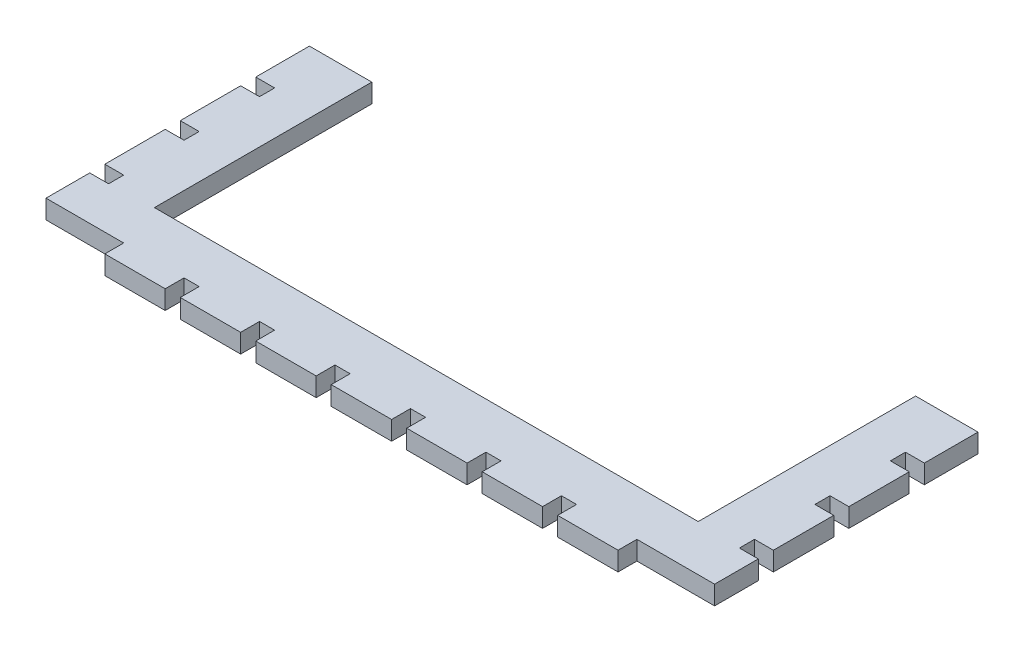
SolidWorks part; units mm, degrees
ref_plane "Front Plane" through (0, 0, 0) normal (0, 0, 1) x (1, 0, 0)
ref_plane "Top Plane" through (0, 0, 0) normal (0, 1, 0) x (1, 0, 0)
ref_plane "Right Plane" through (0, 0, 0) normal (1, 0, 0) x (0, 0, -1)
sketch "Sketch1" plane through (0, 0, 0) normal (0, 1, 0) x (1, 0, 0)
  line L48 (32.1429, 0) -> (32.1429, 6.35)
  line L49 (0, 0) -> (32.1429, 0)
  line L50 (0, 0) -> (0, 6.35)
  line L51 (0, 6.35) -> (32.1429, 6.35)
  line L52 (32.1429, 0) -> (32.1429, 6.35)
  line L53 (0, 0) -> (6.35, 0)
  line L54 (0, 0) -> (0, 32.1429)
  line L55 (0, 32.1429) -> (6.35, 32.1429)
  line L56 (6.35, 0) -> (6.35, 32.1429)
  line L57 (32.1429, 0) -> (64.2857, 0)
  line L58 (64.2857, 0) -> (64.2857, 6.35)
  line L59 (32.1429, 6.35) -> (64.2857, 6.35)
  line L60 (64.2857, 0) -> (64.2857, 6.35)
  line L61 (64.2857, 0) -> (96.4286, 0)
  line L62 (96.4286, 0) -> (96.4286, 6.35)
  line L63 (64.2857, 6.35) -> (96.4286, 6.35)
  line L64 (96.4286, 0) -> (96.4286, 6.35)
  line L65 (96.4286, 0) -> (128.5714, 0)
  line L66 (128.5714, 0) -> (128.5714, 6.35)
  line L67 (96.4286, 6.35) -> (128.5714, 6.35)
  line L72 (128.5714, 0) -> (128.5714, 6.35)
  line L73 (128.5714, 0) -> (160.7143, 0)
  line L74 (160.7143, 0) -> (160.7143, 6.35)
  line L75 (128.5714, 6.35) -> (160.7143, 6.35)
  line L76 (160.7143, 0) -> (160.7143, 6.35)
  line L77 (160.7143, 0) -> (192.8571, 0)
  line L78 (192.8571, 0) -> (192.8571, 6.35)
  line L79 (160.7143, 6.35) -> (192.8571, 6.35)
  line L80 (192.8571, 0) -> (192.8571, 6.35)
  line L81 (192.8571, 0) -> (225, 0)
  line L82 (225, 0) -> (225, 6.35)
  line L83 (192.8571, 6.35) -> (225, 6.35)
  line L84 (0, 32.1429) -> (0, 64.2857)
  line L85 (0, 32.1429) -> (6.35, 32.1429)
  line L86 (6.35, 32.1429) -> (6.35, 64.2857)
  line L87 (0, 64.2857) -> (6.35, 64.2857)
  line L88 (0, 64.2857) -> (0, 96.4286)
  line L89 (0, 64.2857) -> (6.35, 64.2857)
  line L90 (6.35, 64.2857) -> (6.35, 96.4286)
  line L91 (0, 96.4286) -> (6.35, 96.4286)
  line L98 (0, 96.4286) -> (0, 128.5714)
  line L99 (0, 96.4286) -> (6.35, 96.4286)
  line L100 (6.35, 96.4286) -> (6.35, 128.5714)
  line L101 (0, 128.5714) -> (6.35, 128.5714)
  line L102 (0, 128.5714) -> (0, 160.7143)
  line L103 (0, 128.5714) -> (6.35, 128.5714)
  line L104 (6.35, 128.5714) -> (6.35, 160.7143)
  line L105 (0, 160.7143) -> (6.35, 160.7143)
  line L106 (0, 160.7143) -> (0, 192.8571)
  line L107 (0, 160.7143) -> (6.35, 160.7143)
  line L108 (6.35, 160.7143) -> (6.35, 192.8571)
  line L109 (0, 192.8571) -> (6.35, 192.8571)
  line L110 (0, 192.8571) -> (0, 225)
  line L111 (0, 192.8571) -> (6.35, 192.8571)
  line L112 (6.35, 192.8571) -> (6.35, 225)
  line L113 (0, 225) -> (6.35, 225)
  line L114 (112.5, 0) -> (112.5, 671.069) construction
  line L115 (-187.856, 112.5) -> (254.8092, 112.5) construction
  line L116 (225, 32.1429) -> (218.65, 32.1429)
  line L117 (218.65, 0) -> (218.65, 32.1429)
  line L118 (225, 0) -> (218.65, 0)
  line L119 (225, 0) -> (225, 32.1429)
  line L120 (225, 192.8571) -> (218.65, 192.8571)
  line L121 (218.65, 192.8571) -> (218.65, 225)
  line L122 (225, 225) -> (218.65, 225)
  line L123 (225, 192.8571) -> (225, 225)
  line L124 (225, 160.7143) -> (218.65, 160.7143)
  line L125 (218.65, 160.7143) -> (218.65, 192.8571)
  line L126 (225, 192.8571) -> (218.65, 192.8571)
  line L127 (225, 160.7143) -> (225, 192.8571)
  line L128 (225, 32.1429) -> (218.65, 32.1429)
  line L129 (218.65, 32.1429) -> (218.65, 64.2857)
  line L130 (225, 64.2857) -> (218.65, 64.2857)
  line L131 (225, 32.1429) -> (225, 64.2857)
  line L132 (225, 128.5714) -> (218.65, 128.5714)
  line L133 (218.65, 128.5714) -> (218.65, 160.7143)
  line L134 (225, 160.7143) -> (218.65, 160.7143)
  line L135 (225, 128.5714) -> (225, 160.7143)
  line L136 (225, 96.4286) -> (218.65, 96.4286)
  line L137 (218.65, 96.4286) -> (218.65, 128.5714)
  line L138 (225, 128.5714) -> (218.65, 128.5714)
  line L139 (225, 96.4286) -> (225, 128.5714)
  line L140 (225, 64.2857) -> (218.65, 64.2857)
  line L141 (218.65, 64.2857) -> (218.65, 96.4286)
  line L142 (225, 96.4286) -> (218.65, 96.4286)
  line L143 (225, 64.2857) -> (225, 96.4286)
  line L144 (192.8571, 225) -> (225, 225)
  line L145 (225, 225) -> (225, 218.65)
  line L146 (192.8571, 218.65) -> (225, 218.65)
  line L147 (192.8571, 225) -> (192.8571, 218.65)
  line L148 (160.7143, 225) -> (192.8571, 225)
  line L149 (192.8571, 225) -> (192.8571, 218.65)
  line L150 (160.7143, 218.65) -> (192.8571, 218.65)
  line L151 (160.7143, 225) -> (160.7143, 218.65)
  line L152 (128.5714, 225) -> (160.7143, 225)
  line L153 (160.7143, 225) -> (160.7143, 218.65)
  line L154 (128.5714, 218.65) -> (160.7143, 218.65)
  line L155 (128.5714, 225) -> (128.5714, 218.65)
  line L156 (96.4286, 225) -> (128.5714, 225)
  line L157 (128.5714, 225) -> (128.5714, 218.65)
  line L158 (96.4286, 218.65) -> (128.5714, 218.65)
  line L159 (96.4286, 225) -> (96.4286, 218.65)
  line L160 (64.2857, 225) -> (96.4286, 225)
  line L161 (96.4286, 225) -> (96.4286, 218.65)
  line L162 (64.2857, 218.65) -> (96.4286, 218.65)
  line L163 (64.2857, 225) -> (64.2857, 218.65)
  line L164 (32.1429, 225) -> (64.2857, 225)
  line L165 (64.2857, 225) -> (64.2857, 218.65)
  line L166 (32.1429, 218.65) -> (64.2857, 218.65)
  line L167 (32.1429, 225) -> (32.1429, 218.65)
  line L168 (0, 218.65) -> (32.1429, 218.65)
  line L169 (32.1429, 225) -> (32.1429, 218.65)
  line L170 (0, 225) -> (32.1429, 225)
  line L171 (0, 225) -> (0, 218.65)
  point P56 (112.5, 6.35)
  point P58 (6.35, 112.5)
  dimension "D3" = 112.5
  dimension "D4" = 112.5
  dimension "D5" = 6.35
  dimension "D2" = 7
  dimension "D1" = 7
extrude "Boss-Extrude1" add sketch "Sketch1" along normal blind 6.35 contours L168 L112 L108 L104 L100 L90 L86 L56 L51 L59 L63 L67 L75 L79 L83 L117 L129 L141 L137 L133 L125 L121 L146 L150 L154 L158 L162 L166 | L164 L167 L166 L163 | L156 L159 L158 L155 | L148 L151 L150 L147 | L79 L74 L77 L78 | L67 L62 L65 L66 | L59 L48 L57 L58
sketch "Sketch2" plane through (0, 6.35, 0) normal (0, 1, 0) x (1, 0, 0)
  line L0 (218.65, 112.5) -> (6.35, 112.5) construction
  line L1 (218.65, 6.35) -> (218.65, 218.65) construction
  line L2 (6.35, 6.35) -> (6.35, 218.65) construction
  line L3 (160.7143, 225) -> (192.8571, 225) construction
  line L4 (6.35, 112.5) -> (218.65, 112.5)
  line L5 (6.35, 112.5) -> (6.35, 225)
  line L6 (6.35, 225) -> (218.65, 225)
  line L7 (218.65, 112.5) -> (218.65, 225)
extrude "Cut-Extrude1" cut sketch "Sketch2" against normal through all
sketch "Sketch3" plane through (0, 6.35, 0) normal (0, 1, 0) x (1, 0, 0)
  line L1 (6.35, 112.5) -> (218.65, 112.5)
  line L2 (6.35, 112.5) -> (6.35, 95)
  line L3 (6.35, 95) -> (218.65, 95)
  line L4 (218.65, 112.5) -> (218.65, 95)
  line L5 (218.65, 6.35) -> (218.65, 112.5) construction
  line L6 (192.8571, 6.35) -> (218.65, 6.35) construction
  point P5 (218.65, 77.2727)
  point P7 (0, 0)
  dimension "D1" = 88.65
extrude "Cut-Extrude2" cut sketch "Sketch3" against normal up to surface (6.35 mm away) up to face at (112.5, 0, -17.2375)
sketch "Sketch4" plane through (0, 6.35, 0) normal (0, 1, 0) x (1, 0, 0)
  line L0 (6.35, 6.35) -> (6.35, 95) construction
  line L1 (6.35, 26.14) -> (0, 26.14)
  line L2 (6.35, 26.14) -> (6.35, 46.46)
  line L3 (6.35, 46.46) -> (0, 46.46)
  line L4 (0, 26.14) -> (0, 46.46)
  line L5 (6.35, 95) -> (0, 95)
  line L6 (6.35, 51.54) -> (0, 51.54)
  line L7 (6.35, 51.54) -> (6.35, 71.86)
  line L8 (6.35, 71.86) -> (0, 71.86)
  line L9 (0, 51.54) -> (0, 71.86)
  line L10 (6.35, 76.94) -> (0, 76.94)
  line L11 (6.35, 76.94) -> (6.35, 97.26)
  line L12 (6.35, 97.26) -> (0, 97.26)
  line L13 (0, 76.94) -> (0, 97.26)
  line L14 (6.35, 6.35) -> (0, 6.35)
  line L15 (6.35, 6.35) -> (6.35, 21.06)
  line L16 (6.35, 21.06) -> (0, 21.06)
  line L17 (0, 6.35) -> (0, 21.06)
  line L18 (112.5, 0) -> (112.5, 95) construction
  line L19 (96.4286, 0) -> (128.5714, 0) construction
  line L20 (6.35, 95) -> (218.65, 95) construction
  line L21 (225, 6.35) -> (225, 21.06)
  line L22 (218.65, 21.06) -> (225, 21.06)
  line L23 (218.65, 6.35) -> (218.65, 21.06)
  line L24 (218.65, 6.35) -> (225, 6.35)
  line L25 (225, 76.94) -> (225, 97.26)
  line L26 (218.65, 97.26) -> (225, 97.26)
  line L27 (218.65, 76.94) -> (218.65, 97.26)
  line L28 (218.65, 76.94) -> (225, 76.94)
  line L29 (225, 51.54) -> (225, 71.86)
  line L30 (218.65, 71.86) -> (225, 71.86)
  line L31 (218.65, 51.54) -> (218.65, 71.86)
  line L32 (218.65, 51.54) -> (225, 51.54)
  line L33 (218.65, 95) -> (225, 95)
  line L34 (225, 26.14) -> (225, 46.46)
  line L35 (218.65, 46.46) -> (225, 46.46)
  line L36 (218.65, 26.14) -> (218.65, 46.46)
  line L37 (218.65, 26.14) -> (225, 26.14)
  line L38 (225, 95) -> (218.65, 95)
  line L40 (225, 95) -> (218.65, 95)
  line L41 (225, 95) -> (225, 76.94)
  line L42 (225, 76.94) -> (218.65, 76.94)
  line L43 (218.65, 95) -> (218.65, 76.94)
  line M18 (6.35, 95) -> (6.35, 6.35)
  dimension "D1" = 20.32
  dimension "D2" = 5.08
  dimension "D3" = 5.08
  dimension "D4" = 5.08
  dimension "D5" = 14.71
  dimension "D6" = 6.35
extrude "Boss-Extrude2" add sketch "Sketch4" against normal up to surface (6.35 mm away) contours L13 L10 L5 M18 | L9 L6 L8 M18 | L4 L1 L3 M18 | L17 L14 L16 M18 | L41 L40 L43 L42 | L29 L30 L31 L32 | L34 L35 L36 L37 | L21 L22 L23 L24 up to face at (112.5, 0, -15.05)
sketch "Sketch5" plane through (0, 0, 0) normal (0, -1, 0) x (1, 0, 0)
  line L0 (225, -95) -> (0, -95) construction
  line L1 (204, -95) -> (21, -95)
  line L2 (204, -95) -> (204, -21.844)
  line L3 (204, -21.844) -> (21, -21.844)
  line L4 (21, -95) -> (21, -21.844)
  line L5 (112.5, 0) -> (112.5, -133.1244) construction
  line L7 (96.4286, 0) -> (128.5714, 0) construction
  line L8 (0, -46.46) -> (0, -26.14) construction
  line L10 (32.1429, 0) -> (64.2857, 0) construction
  point P9 (112.5, 0)
  point P11 (112.5, -95)
  dimension "D1" = 21
  dimension "D2" = 21.844
extrude "Cut-Extrude3" cut sketch "Sketch5" against normal through all
sketch "Sketch6" plane through (0, 0, 0) normal (0, -1, 0) x (1, 0, 0)
  line L0 (0, -21.06) -> (0, -6.35) construction
  line L1 (225, -6.35) -> (0, -6.35)
  line L2 (225, -6.35) -> (225, 0)
  line L3 (225, 0) -> (0, 0)
  line L4 (0, -6.35) -> (0, 0)
  line L5 (32.1429, 0) -> (64.2857, 0) construction
extrude "Boss-Extrude3" add sketch "Sketch6" against normal up to surface (6.35 mm away) up to face at (112.5, 6.35, -37.5111)
sketch "Sketch7" plane through (0, 0, 0) normal (0, -1, 0) x (1, 0, 0)
  line L0 (0, 0) -> (225, 0) construction
  line L1 (178.54, -6.35) -> (198.86, -6.35)
  line L2 (178.54, -6.35) -> (178.54, 0)
  line L3 (178.54, 0) -> (198.86, 0)
  line L4 (198.86, -6.35) -> (198.86, 0)
  line L5 (153.14, -6.35) -> (153.14, 0)
  line L6 (153.14, -6.35) -> (173.46, -6.35)
  line L7 (173.46, -6.35) -> (173.46, 0)
  line L8 (153.14, 0) -> (173.46, 0)
  line L9 (127.74, -6.35) -> (127.74, 0)
  line L10 (127.74, -6.35) -> (148.06, -6.35)
  line L11 (148.06, -6.35) -> (148.06, 0)
  line L12 (127.74, 0) -> (148.06, 0)
  line L13 (102.34, -6.35) -> (102.34, 0)
  line L14 (102.34, -6.35) -> (122.66, -6.35)
  line L15 (122.66, -6.35) -> (122.66, 0)
  line L16 (102.34, 0) -> (122.66, 0)
  line L17 (76.94, -6.35) -> (76.94, 0)
  line L18 (76.94, -6.35) -> (97.26, -6.35)
  line L19 (97.26, -6.35) -> (97.26, 0)
  line L20 (76.94, 0) -> (97.26, 0)
  line L21 (51.54, -6.35) -> (51.54, 0)
  line L22 (51.54, -6.35) -> (71.86, -6.35)
  line L23 (71.86, -6.35) -> (71.86, 0)
  line L24 (51.54, 0) -> (71.86, 0)
  line L25 (26.14, -6.35) -> (26.14, 0)
  line L26 (26.14, -6.35) -> (46.46, -6.35)
  line L27 (46.46, -6.35) -> (46.46, 0)
  line L28 (26.14, 0) -> (46.46, 0)
  line L30 (178.54, -6.35) -> (173.46, -6.35)
  line L31 (178.54, -6.35) -> (178.54, 0)
  line L32 (178.54, 0) -> (173.46, 0)
  line L33 (173.46, -6.35) -> (173.46, 0)
  line L34 (153.14, -6.35) -> (148.06, -6.35)
  line L35 (153.14, -6.35) -> (153.14, 0)
  line L36 (153.14, 0) -> (148.06, 0)
  line L37 (148.06, -6.35) -> (148.06, 0)
  line L38 (127.74, -6.35) -> (122.66, -6.35)
  line L39 (127.74, -6.35) -> (127.74, 0)
  line L40 (127.74, 0) -> (122.66, 0)
  line L41 (122.66, -6.35) -> (122.66, 0)
  line L42 (102.34, -6.35) -> (97.26, -6.35)
  line L43 (102.34, -6.35) -> (102.34, 0)
  line L44 (102.34, 0) -> (97.26, 0)
  line L45 (97.26, -6.35) -> (97.26, 0)
  line L46 (76.94, -6.35) -> (71.86, -6.35)
  line L47 (76.94, -6.35) -> (76.94, 0)
  line L48 (76.94, 0) -> (71.86, 0)
  line L49 (71.86, -6.35) -> (71.86, 0)
  line L50 (51.54, -6.35) -> (46.46, -6.35)
  line L51 (51.54, -6.35) -> (51.54, 0)
  line L52 (51.54, 0) -> (46.46, 0)
  line L53 (46.46, -6.35) -> (46.46, 0)
  line L54 (198.86, -6.35) -> (225, -6.35)
  line L55 (198.86, -6.35) -> (198.86, 0)
  line L56 (198.86, 0) -> (225, 0)
  line L57 (225, -6.35) -> (225, 0)
  line L58 (26.14, -6.35) -> (0, -6.35)
  line L59 (26.14, -6.35) -> (26.14, 0)
  line L60 (26.14, 0) -> (0, 0)
  line L61 (0, -6.35) -> (0, 0)
  point P31 (112.5, 0)
  point P32 (112.5, 0)
  point P34 (137.9, 0)
  line M27 (225, 0) -> (0, 0)
  dimension "D2" = 25.4
  dimension "D3" = 5.08
  dimension "D4" = 6.35
  dimension "D1" = 7
extrude "Cut-Extrude4" cut sketch "Sketch7" against normal through all contours L30 L2 L7 M27 | L34 L5 L11 M27 | L38 L9 L15 M27 | L42 L13 L19 M27 | L46 L17 L23 M27 | L50 L21 L27 M27 | L55 L54 L57 L56 | L59 L58 L61 L60
